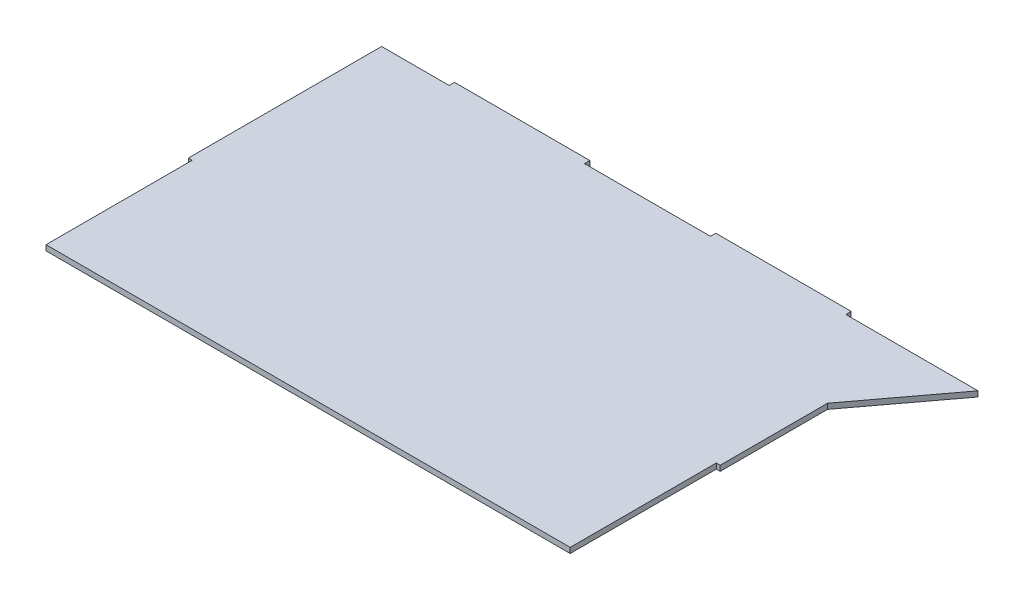
SolidWorks part; units mm, degrees
material "6061-T6 (SS)"
ref_plane "X-Y Datum" through (0, 0, 0) normal (0, 0, 1) x (1, 0, 0)
ref_plane "X-Z Datum" through (0, 0, 0) normal (0, 1, 0) x (1, 0, 0)
ref_plane "Y-Z Datum" through (0, 0, 0) normal (1, 0, 0) x (0, 0, -1)
sketch "Sketch1" plane through (0, 0, 0) normal (0, 0, 1) x (1, 0, 0)
  line L1 (-157.1648, -1.5875) -> (157.1648, -1.5875)
  line L2 (-157.1648, -1.5875) -> (-157.1648, 1.5875)
  line L3 (-157.1648, 1.5875) -> (157.1648, 1.5875)
  line L4 (157.1648, -1.5875) -> (157.1648, 1.5875)
  line L5 (-157.1648, -1.5875) -> (157.1648, 1.5875) construction
  line L6 (-157.1648, 1.5875) -> (157.1648, -1.5875) construction
  point P0 (0, 0)
  dimension "D1" = 314.3296
  dimension "D2" = 3.175
extrude "Boss-Extrude1" add sketch "Sketch1" along normal blind 200.6
sketch "Sketch3" plane through (0, 0, 0) normal (0, 0, -1) x (-1, 0, 0)
  line L0 (-157.1648, 0) -> (-77.1648, 0) construction
  line L1 (-157.1648, -1.5875) -> (-157.1648, 1.5875) construction
  line L2 (-157.1648, 1.5875) -> (157.1648, 1.5875) construction
  line L3 (-117.1648, -1.5875) -> (-37.1648, -1.5875)
  line L4 (-117.1648, -1.5875) -> (-117.1648, 1.5875)
  line L5 (-117.1648, 1.5875) -> (-37.1648, 1.5875)
  line L6 (-37.1648, -1.5875) -> (-37.1648, 1.5875)
  line L7 (-117.1648, -1.5875) -> (-37.1648, 1.5875) construction
  line L8 (-117.1648, 1.5875) -> (-37.1648, -1.5875) construction
  line L14 (-157.1648, 1.5875) -> (-117.1648, 1.5875)
  line L15 (-157.1648, 1.5875) -> (-157.1648, -1.5875)
  line L16 (-157.1648, -1.5875) -> (-117.1648, -1.5875)
  line L17 (-117.1648, 1.5875) -> (-117.1648, -1.5875)
  line L19 (-37.1648, 1.5875) -> (-37.1648, -1.5875)
  dimension "D1" = 40
  dimension "D2" = 80
sketch "Sketch5" plane through (0, 1.5875, 0) normal (0, 1, 0) x (1, 0, 0)
  line L1 (-157.1648, -200.6) -> (-154.8788, -200.6)
  line L3 (-157.1648, -200.6) -> (-157.1648, -114.24)
  line L5 (-157.1648, -114.24) -> (-154.8788, -114.24)
  line L6 (-154.8788, -200.6) -> (-154.8788, -114.24)
  dimension "D1" = 86.36
  dimension "D2" = 2.286
extrude "Cut-Extrude2" cut sketch "Sketch5" against normal blind 3.175 and the other way through all
mirror "Mirror1" about plane through (0, 0, 0) normal (1, 0, 0) of "Cut-Extrude2"
sketch "Sketch6" plane through (0, 1.5875, 0) normal (0, 1, 0) x (1, 0, 0)
  line L6 (-157.1648, -180.28) -> (-80.9648, -180.28)
  line L7 (-157.1648, -180.28) -> (-157.1648, -200.6)
  line L8 (-157.1648, -200.6) -> (-80.9648, -200.6)
  line L9 (-80.9648, -180.28) -> (-80.9648, -200.6)
  line L10 (154.8788, -200.6) -> (-154.8788, -200.6) construction
  line L11 (-157.1648, -114.24) -> (-157.1648, 0) construction
  line L13 (154.8788, -200.6) -> (-80.9648, -200.6)
  line L14 (154.8788, -200.6) -> (154.8788, -180.28)
  line L15 (154.8788, -180.28) -> (-80.9648, -180.28)
  line L16 (-80.9648, -200.6) -> (-80.9648, -180.28)
  line M18 (-154.8788, -114.24) -> (-154.8788, -200.6)
  line M19 (-154.8788, -200.6) -> (154.8788, -200.6)
  dimension "D1" = 76.2
  dimension "D2" = 20.32
extrude "Cut-Extrude4" [suppressed] cut sketch "Sketch6" against normal through all contours L9 L6 M18 M19
sketch "Sketch7" [suppressed] plane through (0, 1.5875, 0) normal (0, 1, 0) x (1, 0, 0)
  line L1 (-81.2823, -215.455) -> (155.1963, -215.455)
  line L2 (-81.2823, -215.455) -> (-81.2823, -235.775)
  line L3 (-81.2823, -235.775) -> (155.1963, -235.775)
  line L4 (155.1963, -215.455) -> (155.1963, -235.775)
extrude "Cut-Extrude5" [suppressed] cut sketch "Sketch7" against normal through all
sketch "Sketch8" [suppressed] plane through (0, 1.5875, 0) normal (0, 1, 0) x (1, 0, 0)
  line L0 (155.1963, -235.775) -> (-155.1963, -235.775) construction
  line L1 (157.4823, -215.455) -> (81.2823, -215.455)
  line L2 (157.4823, -215.455) -> (157.4823, -235.775)
  line L3 (157.4823, -235.775) -> (81.2823, -235.775)
  line L4 (81.2823, -215.455) -> (81.2823, -235.775)
  line L5 (157.4823, -117.411) -> (157.4823, -3.175) construction
  dimension "D1" = 20.32
  dimension "D2" = 76.2
extrude "Cut-Extrude6" [suppressed] cut sketch "Sketch8" against normal through all
sketch "Sketch9" [suppressed] plane through (0, 0, 215.455) normal (0, 0, 1) x (1, 0, 0)
  line L4 (155.1963, 1.5875) -> (-155.1963, 1.5875)
  line L5 (-155.1963, 1.5875) -> (-155.1963, -1.5875)
  line L6 (-155.1963, -1.5875) -> (155.1963, -1.5875)
  line L7 (155.1963, -1.5875) -> (155.1963, 1.5875)
  line L8 (155.1963, 1.5875) -> (-155.1963, 1.5875)
  line L9 (-155.1963, 1.5875) -> (-155.1963, -1.5875)
  line L10 (-155.1963, -1.5875) -> (155.1963, -1.5875)
  line L11 (155.1963, -1.5875) -> (155.1963, 1.5875)
  dimension "D1" = 0
extrude "Cut-Extrude7" [suppressed] cut sketch "Sketch9" against normal blind 11.68
extrude "Boss-Extrude2" add sketch "Sketch3" along normal blind 3.175
pattern_linear "LPattern2" count 2 spacing 154.43 along (-1, 0, 0) of "Boss-Extrude2"
sketch "Sketch10" plane through (0, -1.5875, 0) normal (0, -1, 0) x (1, 0, 0)
  line L8 (157.1648, 0) -> (195.2648, 0)
  line L9 (195.2648, 0) -> (157.1648, 50.8)
  line L10 (157.1648, 114.24) -> (157.1648, 0) construction
  line L11 (157.1648, 50.8) -> (157.1648, 0)
  dimension "D1" = 50.8
  dimension "D2" = 38.1
extrude "Boss-Extrude3" add sketch "Sketch10" against normal blind 3.175
sketch "Sketch11" [suppressed] plane through (0, 0, 0) normal (0, 0, -1) x (-1, 0, 0)
  line L1 (37.2652, -1.5875) -> (117.2652, -1.5875)
  line L2 (37.2652, -1.5875) -> (37.2652, 1.5875)
  line L3 (37.2652, 1.5875) -> (117.2652, 1.5875)
  line L4 (117.2652, -1.5875) -> (117.2652, 1.5875)
  line L5 (-117.1668, -1.5875) -> (-37.1668, -1.5875)
  line L6 (-117.1668, -1.5875) -> (-117.1668, 1.5875)
  line L7 (-117.1668, 1.5875) -> (-37.1668, 1.5875)
  line L8 (-37.1668, -1.5875) -> (-37.1668, 1.5875)
extrude "Boss-Extrude4" [suppressed] add sketch "Sketch11" along normal blind 3.175
